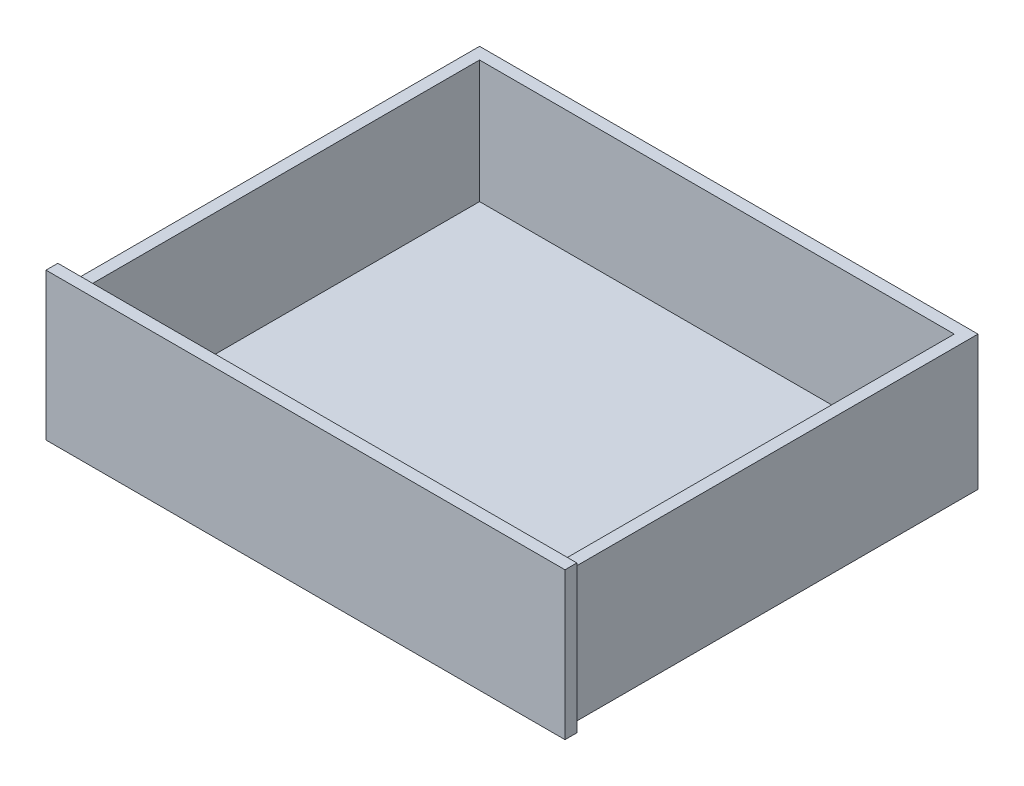
SolidWorks part; units mm, degrees
material "Maple"
ref_plane "Front Plane" through (0, 0, 0) normal (0, 0, 1) x (1, 0, 0)
ref_plane "Top Plane" through (0, 0, 0) normal (0, 1, 0) x (1, 0, 0)
ref_plane "Right Plane" through (0, 0, 0) normal (1, 0, 0) x (0, 0, -1)
sketch "Sketch1" plane through (0, 0, 0) normal (0, 1, 0) x (1, 0, 0)
  line L1 (-315, -260) -> (315, -260)
  line L2 (-315, -260) -> (-315, 260)
  line L3 (-315, 260) -> (315, 260)
  line L4 (315, -260) -> (315, 260)
  line L5 (-315, -260) -> (315, 260) construction
  line L6 (-315, 260) -> (315, -260) construction
  point P0 (0, 0)
  dimension "D1" = 630
  dimension "D2" = 520
extrude "Extrusion" add sketch "Sketch1" along normal blind 170
shell "Drawer's interior" thickness 15
sketch "Sketch2" plane through (0, 0, 260) normal (0, 0, 1) x (1, 0, 0)
  line L0 (-315, 0) -> (315, 0) construction
  line L1 (-351.5, -5) -> (351.5, -5)
  line L2 (-351.5, -5) -> (-351.5, 175)
  line L3 (-351.5, 175) -> (351.5, 175)
  line L4 (351.5, -5) -> (351.5, 175)
  line L5 (-351.5, -5) -> (351.5, 175) construction
  line L6 (-351.5, 175) -> (351.5, -5) construction
  line L7 (315, 170) -> (315, 0) construction
  point P0 (0, 85)
  point P5 (0, 0)
  point P8 (0, 0)
  point P14 (315, 85)
  dimension "D1" = 703
  dimension "D2" = 180
extrude "Boss-Extrude2" [suppressed] add sketch "Sketch2" along normal blind 17 contours L4 L3 L2 L1
sketch "Sketch3" plane through (0, 0, 260) normal (0, 0, 1) x (1, 0, 0)
  line L0 (315, 170) -> (315, 0) construction
  line L1 (-328, 186) -> (328, 186)
  line L2 (-328, 186) -> (-328, 0)
  line L4 (328, 186) -> (328, 0)
  line L5 (-315, 170) -> (-315, 0) construction
  line L6 (-315, 170) -> (315, 170) construction
  line L8 (-328, 0) -> (328, 0)
  line L9 (-315, 0) -> (315, 0) construction
  dimension "D1" = 13
  dimension "D2" = 13
  dimension "D3" = 16
  dimension "D4" = 0
extrude "Boss-Extrude3" add sketch "Sketch3" along normal blind 15
